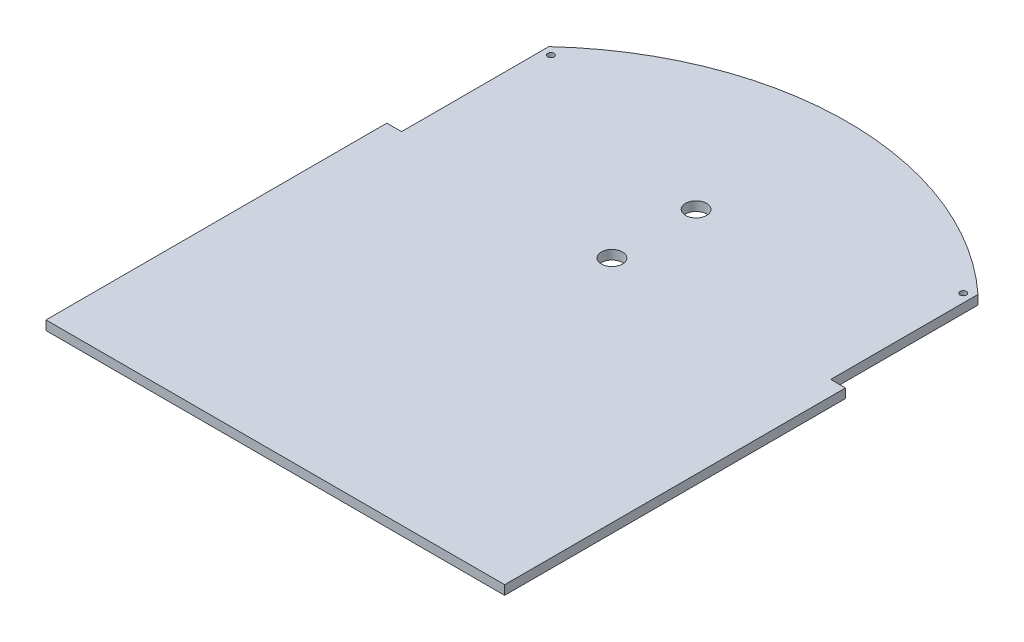
SolidWorks part; units mm, degrees
ref_plane "Front Plane" through (0, 0, 0) normal (0, 0, 1) x (1, 0, 0)
ref_plane "Top Plane" through (0, 0, 0) normal (0, 1, 0) x (1, 0, 0)
ref_plane "Right Plane" through (0, 0, 0) normal (1, 0, 0) x (0, 0, -1)
sketch "Sketch1" plane through (0, 0, 0) normal (0, 1, 0) x (1, 0, 0)
  line L0 (-54.5, 0) -> (-54.5, 81)
  line L1 (-55, 0) -> (55, 0) construction
  line L2 (-54.5, 81) -> (-51, 81)
  line L3 (-51, 81) -> (-51, 116)
  line L5 (51, 116) -> (51, 81)
  line L6 (51, 81) -> (54.5, 81)
  line L7 (54.5, 81) -> (54.5, 0)
  line L8 (54.5, 0) -> (-54.5, 0)
  line L9 (-27.3914, 136) -> (24.5862, 136) construction
  line L10 (-179.8441, 251.4596) -> (243.4892, 251.4596) construction
  arc A0 (-51, 116) -> (51, 116) centre (0, 60.975) cw
  point P9 (0, 0)
  dimension "D4" = 20
  dimension "D1" = 109
  dimension "D2" = 81
  dimension "D3" = 3.5
  dimension "D5" = 35
extrude "Boss-Extrude1" add sketch "Sketch1" along normal blind 2.2
sketch "Sketch2" plane through (0, 2.2, 0) normal (0, 1, 0) x (1, 0, 0)
  line L0 (-51, 116) -> (-51, 81) construction
  line L2 (-55, 0) -> (55, 0) construction
  line L3 (0, -55) -> (0, 55) construction
  circle A0 centre (-49, 114.5) radius 0.75
  circle A3 centre (0, 100) radius 2.5
  circle A4 centre (0, 80) radius 2.5
  dimension "D1" = 1.5
  dimension "D3" = 1.5
  dimension "D4" = 5
  dimension "D2" = 2
  dimension "D5" = 20
  dimension "D7" = 80
extrude "Cut-Extrude1" cut sketch "Sketch2" against normal blind 10
mirror "Mirror1" about plane through (0, 0, 0) normal (1, 0, 0) of "Cut-Extrude1"
